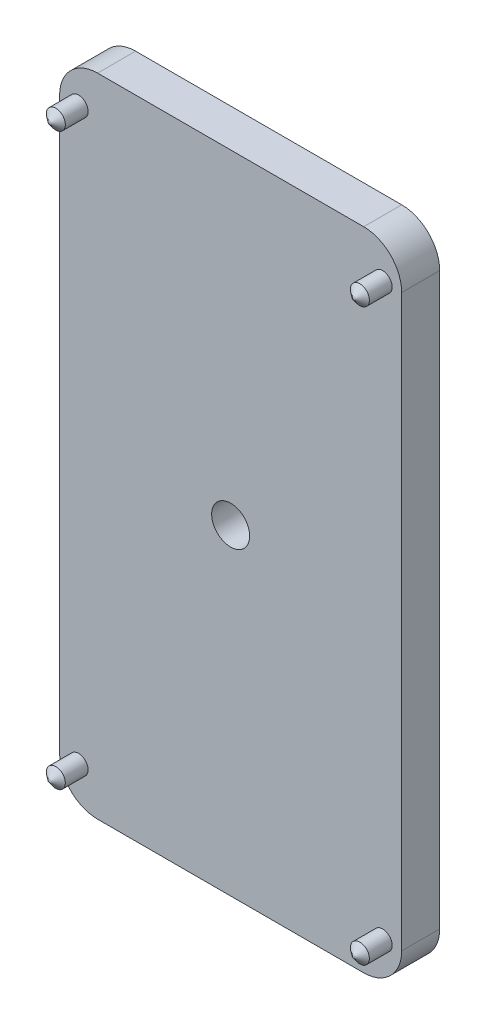
SolidWorks part; units mm, degrees
ref_plane "Front Plane" through (0, 0, 0) normal (0, 0, 1) x (1, 0, 0)
ref_plane "Top Plane" through (0, 0, 0) normal (0, 1, 0) x (1, 0, 0)
ref_plane "Right Plane" through (0, 0, 0) normal (1, 0, 0) x (0, 0, -1)
sketch "Sketch2" plane through (0, 0, 0) normal (0, 0, 1) x (1, 0, 0)
  line L1 (0, 0) -> (90, 0)
  line L2 (0, 0) -> (0, 170)
  line L3 (0, 170) -> (90, 170)
  line L4 (90, 0) -> (90, 170)
  dimension "D1" = 90
  dimension "D2" = 170
extrude "Boss-Extrude1" add sketch "Sketch2" along normal blind 10
sketch "Sketch3" plane through (0, 0, 10) normal (0, 0, 1) x (1, 0, 0)
  circle A0 centre (5, 160) radius 2.5
  circle A1 centre (85, 160) radius 2.5
  circle A2 centre (85, 10) radius 2.5
  circle A3 centre (5, 10) radius 2.5
extrude "Boss-Extrude4" add sketch "Sketch3" along normal blind 6
sketch "Sketch8" plane through (0, 0, 16) normal (0, 0, 1) x (1, 0, 0)
  circle A0 centre (5, 160) radius 2.5
  circle A1 centre (85, 160) radius 2.5
  circle A2 centre (85, 10) radius 2.5
  circle A3 centre (5, 10) radius 2.5
extrude "Boss-Extrude5" add sketch "Sketch8" along normal blind 2 draft 52
sketch "Sketch9" plane through (0, 0, 0) normal (0, 0, -1) x (-1, 0, 0)
  circle A0 centre (-45, 150) radius 2.5
extrude "Boss-Extrude6" add sketch "Sketch9" along normal blind 15
sketch "Sketch10" plane through (0, 0, 0) normal (0, 0, -1) x (-1, 0, 0)
  circle A2 centre (-45, 84.511) radius 5
extrude "Cut-Extrude3" cut sketch "Sketch10" against normal blind 15
fillet "Fillet1" radius 10 1 edges at (90, 170, 5)
fillet "Fillet2" radius 10 1 edges at (0, 170, 5)
fillet "Fillet3" radius 10 1 edges at (0, 0, 5)
fillet "Fillet4" radius 10 1 edges at (90, 0, 5)
